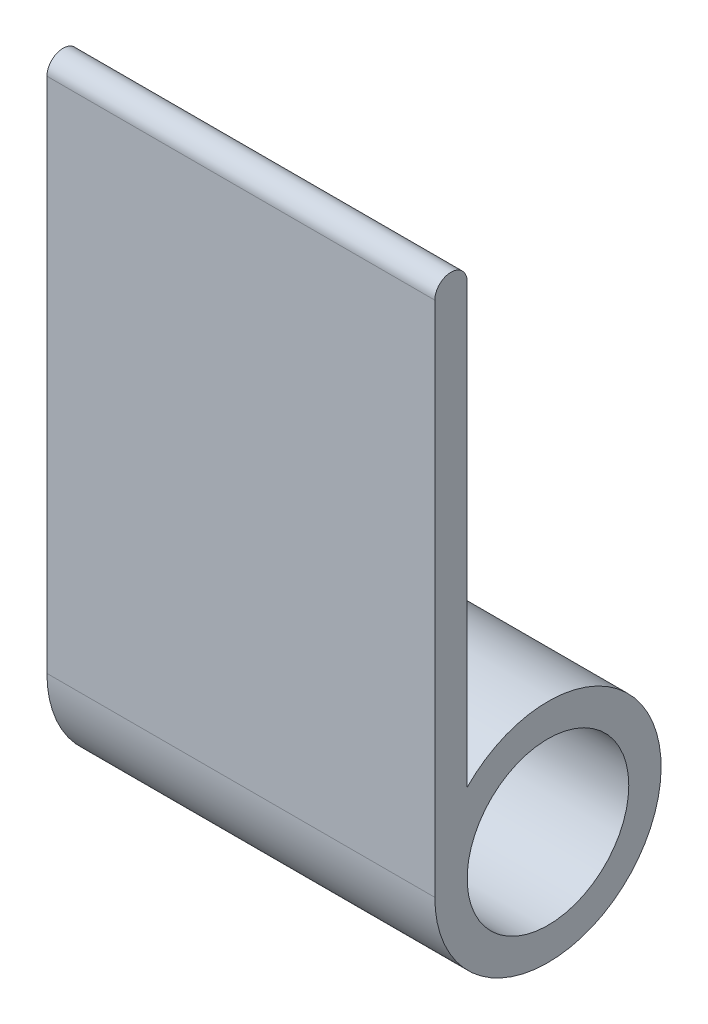
SolidWorks part; units mm, degrees
ref_plane "Front Plane" through (0, 0, 0) normal (0, 0, 1) x (1, 0, 0)
ref_plane "Top Plane" through (0, 0, 0) normal (0, 1, 0) x (1, 0, 0)
ref_plane "Right Plane" through (0, 0, 0) normal (1, 0, 0) x (0, 0, -1)
sketch "Sketch1" plane through (0, 0, 0) normal (1, 0, 0) x (0, 0, -1)
  line L1 (-17.5, 0) -> (-17.5, 80)
  line L2 (-12.5, 80) -> (-12.5, 12.2474)
  circle A0 centre (0, 0) radius 12.5
  circle A1 centre (0, 0) radius 17.5 construction
  arc A2 (-17.5, 80) -> (-12.5, 80) centre (-15, 80) cw
  arc A3 (-17.5, 0) -> (-12.5, 12.2474) centre (0, 0) ccw
  dimension "D1" = 25
  dimension "D4" = 80
  dimension "D2" = 5
  dimension "D3" = 5
extrude "Boss-Extrude1" add sketch "Sketch1" along normal blind 60
sketch "Sketch2" plane through (0, 0, 0) normal (1, 0, 0) x (0, 0, -1)
  line L0 (2.5, 33.3205) -> (-12.5, 33.3205) construction
  line L2 (-12.5, 12.2474) -> (-12.5, 80) construction
  line L3 (2.5, 33.3205) -> (2.5, 17.3205) construction
  line L4 (2.5, 41.9205) -> (-12.5, 41.9205)
  line L5 (2.5, 24.7205) -> (2.5, 17.3205)
  line L8 (-17.5, 80) -> (-17.5, 0)
  line L9 (-12.5, 12.2474) -> (-12.5, 80)
  line L10 (-17.5, 80) -> (-17.5, 0)
  line L11 (-12.5, 12.2474) -> (-12.5, 80)
  circle A0 centre (2.5, 33.3205) radius 5.6
  arc A1 (-17.5, 0) -> (-12.5, 12.2474) centre (0, 0) ccw construction
  circle A2 centre (2.5, 33.3205) radius 8.6 construction
  arc A3 (2.5, 41.9205) -> (2.5, 24.7205) centre (2.5, 33.3205) cw
  arc A6 (-12.5, 80) -> (-17.5, 80) centre (-15, 80) ccw
  arc A7 (-17.5, 0) -> (-12.5, 12.2474) centre (0, 0) ccw
  arc A8 (-12.5, 80) -> (-17.5, 80) centre (-15, 80) ccw
  arc A9 (-17.5, 0) -> (-12.5, 12.2474) centre (0, 0) ccw
  dimension "D1" = 11.2
  dimension "D4" = 3
  dimension "D2" = 15
  dimension "D3" = 16
  dimension "D5" = 0
extrude "Boss-Extrude2" add sketch "Sketch2" along normal blind 5 contours A9 L5 A3 L4 L11 A0
